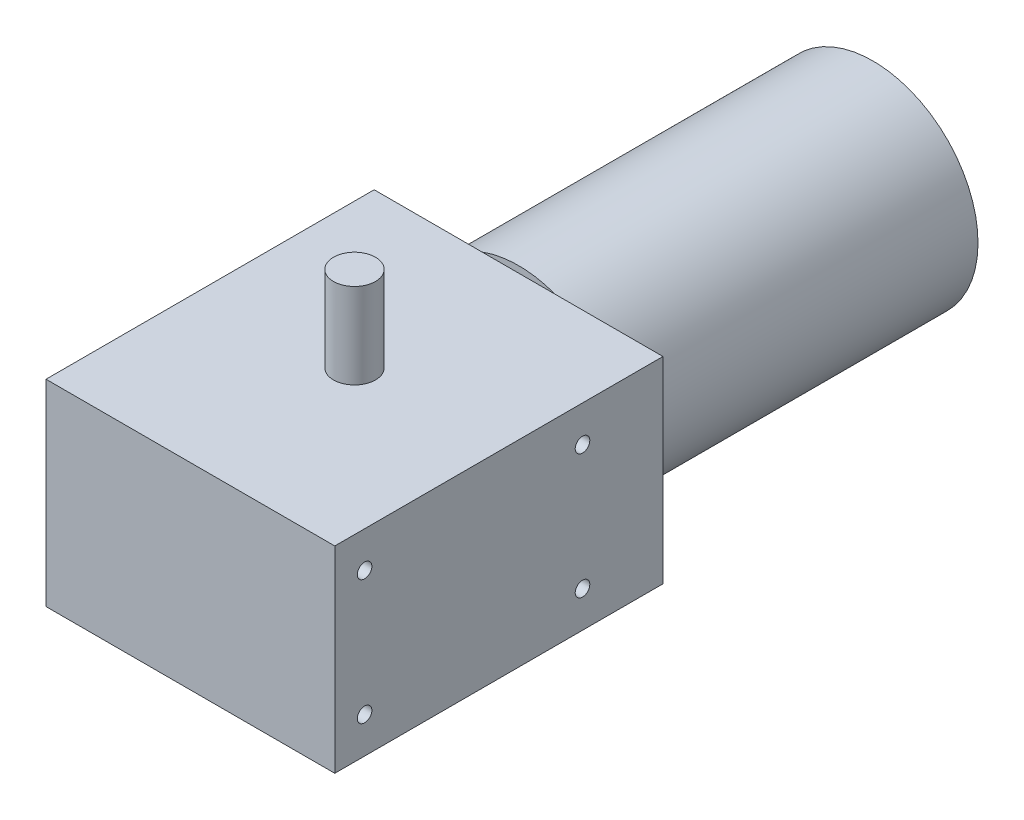
SolidWorks part; units mm, degrees
ref_plane "Alzado" through (0, 0, 0) normal (0, 0, 1) x (1, 0, 0)
ref_plane "Planta" through (0, 0, 0) normal (0, 1, 0) x (1, 0, 0)
ref_plane "Vista lateral" through (0, 0, 0) normal (1, 0, 0) x (0, 0, -1)
sketch "Croquis1" plane through (0, 0, 0) normal (0, 0, 1) x (1, 0, 0)
  line L1 (-110, -75) -> (110, -75)
  line L2 (-110, -75) -> (-110, 75)
  line L3 (-110, 75) -> (110, 75)
  line L4 (110, -75) -> (110, 75)
  line L5 (-110, -75) -> (110, 75) construction
  line L6 (-110, 75) -> (110, -75) construction
  point P0 (0, 0)
  dimension "D1" = 220
  dimension "D2" = 150
extrude "Saliente-Extruir1" add sketch "Croquis1" along normal mid plane 250
sketch "Croquis2" plane through (0, 0, 0) normal (0, 1, 0) x (1, 0, 0)
  circle A0 centre (0, 0) radius 16
  point P3 (0, 0)
  dimension "D1" = 32
extrude "Saliente-Extruir2" add sketch "Croquis2" along normal mid plane 280
sketch "Croquis3" plane through (110, 0, 0) normal (1, 0, 0) x (0, 0, -1)
  line L0 (116.819, 0) -> (-143.6019, 0) construction
  line L1 (0, 64.6778) -> (0, -65.2477) construction
  line L2 (-125, -75) -> (-125, 75) construction
  line L3 (63.7, 47.5) -> (63.7, -47.5) construction
  line L4 (63.7, -47.5) -> (-102.3, -47.5) construction
  line L5 (-102.3, 47.5) -> (63.7, 47.5) construction
  circle A0 centre (-102.3, 47.5) radius 5.5563
  circle A1 centre (-102.3, -47.5) radius 5.5563
  circle A2 centre (63.7, 47.5) radius 5.5563
  circle A3 centre (63.7, -47.5) radius 5.5563
  dimension "D2" = 11.1125
  dimension "D1" = 47.5
  dimension "D3" = 22.7
  dimension "D4" = 166
extrude "Cortar-Extruir1" cut sketch "Croquis3" against normal blind 200
sketch "Croquis4" plane through (0, 0, -125) normal (0, 0, -1) x (-1, 0, 0)
  circle A0 centre (0, 0) radius 80
  dimension "D1" = 160
extrude "Saliente-Extruir3" add sketch "Croquis4" along normal blind 270
